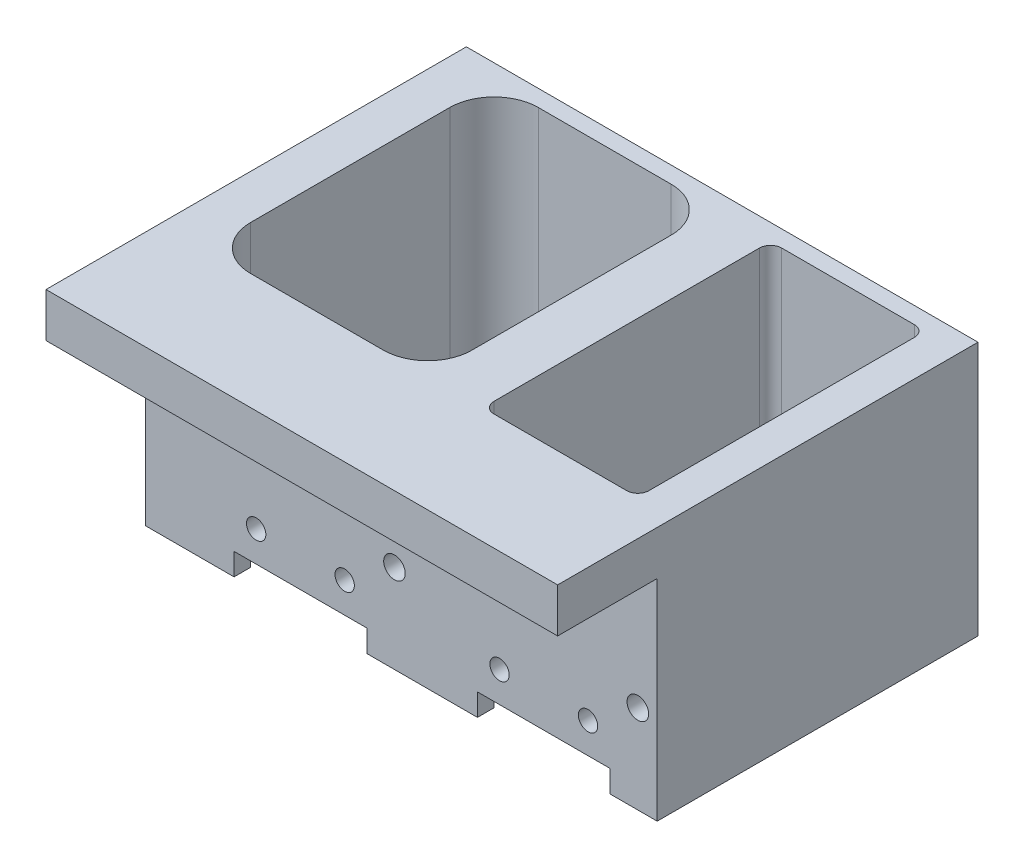
SolidWorks part; units mm, degrees
ref_plane "Front Plane" through (0, 0, 0) normal (0, 0, 1) x (1, 0, 0)
ref_plane "Top Plane" through (0, 0, 0) normal (0, 1, 0) x (1, 0, 0)
ref_plane "Right Plane" through (0, 0, 0) normal (1, 0, 0) x (0, 0, -1)
sketch "Sketch1" plane through (0, 0, 0) normal (0, 1, 0) x (1, 0, 0)
  line L1 (202.5, -147.5) -> (-202.5, -147.5)
  line L2 (202.5, -147.5) -> (202.5, 147.5)
  line L3 (202.5, 147.5) -> (-202.5, 147.5)
  line L4 (-202.5, -147.5) -> (-202.5, 147.5)
  line L5 (202.5, -147.5) -> (-202.5, 147.5) construction
  line L6 (202.5, 147.5) -> (-202.5, -147.5) construction
  point P0 (0, 0)
  dimension "D1" = 405
  dimension "D2" = 295
extrude "Boss-Extrude1" add sketch "Sketch1" along normal blind 53
sketch "Sketch3" plane through (0, 0, 0) normal (0, -1, 0) x (-1, 0, 0)
  line L23 (184.5, -129.5) -> (184.5, 129.5)
  line L24 (184.5, 129.5) -> (-184.5, 129.5)
  line L25 (-184.5, 129.5) -> (-184.5, -129.5)
  line L26 (-184.5, -129.5) -> (184.5, -129.5)
  line L27 (184.5, -129.5) -> (184.5, 129.5)
  line L28 (184.5, 129.5) -> (-184.5, 129.5)
  line L29 (-184.5, 129.5) -> (-184.5, -129.5)
  line L30 (-184.5, -129.5) -> (184.5, -129.5)
  dimension "D1" = 18
extrude "Cut-Extrude2" cut sketch "Sketch3" against normal blind 45 flip side to cut
sketch "Sketch2" plane through (0, 53, 0) normal (0, 1, 0) x (1, 0, 0)
  line L1 (-173.5, -126.5) -> (-105.5, -126.5)
  line L2 (-181.5, -118.5) -> (-181.5, -49.5)
  line L3 (-173.5, -41.5) -> (-105.5, -41.5)
  line L4 (-97.5, -118.5) -> (-97.5, -49.5)
  line L5 (-173.5, -31.5) -> (-105.5, -31.5)
  line L6 (-181.5, -23.5) -> (-181.5, 40.5)
  line L7 (-173.5, 48.5) -> (-105.5, 48.5)
  line L8 (-181.5, 126.5) -> (-181.5, -126.5)
  line L9 (-181.5, -126.5) -> (181.5, -126.5)
  line L10 (181.5, -126.5) -> (181.5, 126.5)
  line L11 (181.5, 126.5) -> (-181.5, 126.5)
  line L12 (-181.5, 126.5) -> (-181.5, -126.5) construction
  line L13 (-181.5, -126.5) -> (181.5, -126.5) construction
  line L14 (181.5, -126.5) -> (181.5, 126.5) construction
  line L15 (181.5, 126.5) -> (-181.5, 126.5) construction
  line L16 (-97.5, -23.5) -> (-97.5, 40.5)
  line L17 (-173.5, 126.5) -> (-105.5, 126.5)
  line L18 (-181.5, 118.5) -> (-181.5, 66.5)
  line L19 (-173.5, 58.5) -> (-105.5, 58.5)
  line L20 (-97.5, 118.5) -> (-97.5, 66.5)
  line L21 (173.5, -126.5) -> (115.5, -126.5)
  line L22 (181.5, -118.5) -> (181.5, 7.5)
  line L23 (173.5, 15.5) -> (115.5, 15.5)
  line L24 (107.5, -118.5) -> (107.5, 7.5)
  line L25 (173.5, 126.5) -> (107.5, 126.5)
  line L26 (181.5, 118.5) -> (181.5, 33.5)
  line L27 (173.5, 25.5) -> (107.5, 25.5)
  line L28 (99.5, 118.5) -> (99.5, 33.5)
  line L29 (81.5, 126.5) -> (20.5, 126.5)
  line L30 (89.5, 118.5) -> (89.5, -7.5)
  line L31 (81.5, -15.5) -> (20.5, -15.5)
  line L32 (12.5, 118.5) -> (12.5, -7.5)
  line L33 (-9.5, 126.5) -> (-31.5, 126.5)
  line L34 (-1.5, 118.5) -> (-1.5, 11.5)
  line L35 (-9.5, 3.5) -> (-31.5, 3.5)
  line L36 (-39.5, 118.5) -> (-39.5, 11.5)
  line L37 (-57.5, 126.5) -> (-79.5, 126.5)
  line L38 (-49.5, 118.5) -> (-49.5, 11.5)
  line L39 (-57.5, 3.5) -> (-79.5, 3.5)
  line L40 (-87.5, 118.5) -> (-87.5, 11.5)
  line L41 (-79.5, -15.5) -> (-55.5, -15.5)
  line L42 (-81.5, -17.5) -> (-81.5, -65.5)
  line L43 (-79.5, -67.5) -> (-55.5, -67.5)
  line L44 (-53.5, -17.5) -> (-53.5, -65.5)
  line L45 (-73.5, -126.5) -> (-49.5, -126.5)
  line L46 (-81.5, -118.5) -> (-81.5, -82.5)
  line L47 (-73.5, -74.5) -> (-49.5, -74.5)
  line L48 (-41.5, -118.5) -> (-41.5, -82.5)
  line L49 (-35.5, -15.5) -> (-11.5, -15.5)
  line L50 (-43.5, -23.5) -> (-43.5, -59.5)
  line L51 (-35.5, -67.5) -> (-11.5, -67.5)
  line L52 (-3.5, -23.5) -> (-3.5, -59.5)
  line L53 (-29.5, -74.5) -> (-5.5, -74.5)
  line L54 (-31.5, -76.5) -> (-31.5, -124.5)
  line L55 (-29.5, -126.5) -> (-5.5, -126.5)
  line L56 (-3.5, -76.5) -> (-3.5, -124.5)
  line L57 (89.5, -126.5) -> (19.5, -126.5)
  line L58 (97.5, -118.5) -> (97.5, -33.5)
  line L59 (89.5, -25.5) -> (19.5, -25.5)
  line L60 (11.5, -118.5) -> (11.5, -33.5)
  arc A0 (-79.5, 126.5) -> (-87.5, 118.5) centre (-79.5, 118.5) ccw
  arc A1 (-79.5, 3.5) -> (-87.5, 11.5) centre (-79.5, 11.5) cw
  arc A2 (-49.5, 11.5) -> (-57.5, 3.5) centre (-57.5, 11.5) cw
  arc A3 (-57.5, 126.5) -> (-49.5, 118.5) centre (-57.5, 118.5) cw
  arc A4 (-31.5, 126.5) -> (-39.5, 118.5) centre (-31.5, 118.5) ccw
  arc A5 (-31.5, 3.5) -> (-39.5, 11.5) centre (-31.5, 11.5) cw
  arc A6 (-1.5, 11.5) -> (-9.5, 3.5) centre (-9.5, 11.5) cw
  arc A7 (-9.5, 126.5) -> (-1.5, 118.5) centre (-9.5, 118.5) cw
  arc A8 (20.5, 126.5) -> (12.5, 118.5) centre (20.5, 118.5) ccw
  arc A9 (20.5, -15.5) -> (12.5, -7.5) centre (20.5, -7.5) cw
  arc A10 (89.5, -7.5) -> (81.5, -15.5) centre (81.5, -7.5) cw
  arc A11 (81.5, 126.5) -> (89.5, 118.5) centre (81.5, 118.5) cw
  arc A12 (107.5, 126.5) -> (99.5, 118.5) centre (107.5, 118.5) ccw
  arc A13 (173.5, 126.5) -> (181.5, 118.5) centre (173.5, 118.5) cw
  arc A14 (181.5, 33.5) -> (173.5, 25.5) centre (173.5, 33.5) cw
  arc A15 (107.5, 25.5) -> (99.5, 33.5) centre (107.5, 33.5) cw
  arc A16 (115.5, 15.5) -> (107.5, 7.5) centre (115.5, 7.5) ccw
  arc A17 (181.5, 7.5) -> (173.5, 15.5) centre (173.5, 7.5) ccw
  arc A18 (173.5, -126.5) -> (181.5, -118.5) centre (173.5, -118.5) ccw
  arc A19 (115.5, -126.5) -> (107.5, -118.5) centre (115.5, -118.5) cw
  arc A20 (89.5, -126.5) -> (97.5, -118.5) centre (89.5, -118.5) ccw
  arc A21 (97.5, -33.5) -> (89.5, -25.5) centre (89.5, -33.5) ccw
  arc A22 (19.5, -25.5) -> (11.5, -33.5) centre (19.5, -33.5) ccw
  arc A23 (19.5, -126.5) -> (11.5, -118.5) centre (19.5, -118.5) cw
  arc A28 (-43.5, -59.5) -> (-35.5, -67.5) centre (-35.5, -59.5) ccw
  arc A29 (-11.5, -67.5) -> (-3.5, -59.5) centre (-11.5, -59.5) ccw
  arc A30 (-11.5, -15.5) -> (-3.5, -23.5) centre (-11.5, -23.5) cw
  arc A31 (-35.5, -15.5) -> (-43.5, -23.5) centre (-35.5, -23.5) ccw
  arc A36 (-49.5, -74.5) -> (-41.5, -82.5) centre (-49.5, -82.5) cw
  arc A37 (-49.5, -126.5) -> (-41.5, -118.5) centre (-49.5, -118.5) ccw
  arc A38 (-73.5, -126.5) -> (-81.5, -118.5) centre (-73.5, -118.5) cw
  arc A39 (-81.5, -82.5) -> (-73.5, -74.5) centre (-73.5, -82.5) cw
  arc A40 (-105.5, -41.5) -> (-97.5, -49.5) centre (-105.5, -49.5) cw
  arc A41 (-105.5, -126.5) -> (-97.5, -118.5) centre (-105.5, -118.5) ccw
  arc A42 (-173.5, -126.5) -> (-181.5, -118.5) centre (-173.5, -118.5) cw
  arc A43 (-181.5, -49.5) -> (-173.5, -41.5) centre (-173.5, -49.5) cw
  arc A44 (-105.5, 48.5) -> (-97.5, 40.5) centre (-105.5, 40.5) cw
  arc A45 (-105.5, -31.5) -> (-97.5, -23.5) centre (-105.5, -23.5) ccw
  arc A46 (-173.5, -31.5) -> (-181.5, -23.5) centre (-173.5, -23.5) cw
  arc A47 (-181.5, 40.5) -> (-173.5, 48.5) centre (-173.5, 40.5) cw
  arc A48 (-105.5, 126.5) -> (-97.5, 118.5) centre (-105.5, 118.5) cw
  arc A49 (-105.5, 58.5) -> (-97.5, 66.5) centre (-105.5, 66.5) ccw
  arc A50 (-181.5, 66.5) -> (-173.5, 58.5) centre (-173.5, 66.5) ccw
  arc A51 (-173.5, 126.5) -> (-181.5, 118.5) centre (-173.5, 118.5) ccw
  arc A52 (-81.5, -17.5) -> (-79.5, -15.5) centre (-79.5, -17.5) cw
  arc A53 (-79.5, -67.5) -> (-81.5, -65.5) centre (-79.5, -65.5) cw
  arc A54 (-53.5, -65.5) -> (-55.5, -67.5) centre (-55.5, -65.5) cw
  arc A55 (-55.5, -15.5) -> (-53.5, -17.5) centre (-55.5, -17.5) cw
  arc A56 (-3.5, -76.5) -> (-5.5, -74.5) centre (-5.5, -76.5) ccw
  arc A57 (-5.5, -126.5) -> (-3.5, -124.5) centre (-5.5, -124.5) ccw
  arc A58 (-31.5, -124.5) -> (-29.5, -126.5) centre (-29.5, -124.5) ccw
  arc A59 (-31.5, -76.5) -> (-29.5, -74.5) centre (-29.5, -76.5) cw
  point P54 (-87.5, 126.5)
  point P57 (-87.5, 3.5)
  point P62 (-49.5, 126.5)
  point P65 (-39.5, 126.5)
  point P72 (-1.5, 126.5)
  point P75 (12.5, 126.5)
  point P82 (89.5, 126.5)
  point P85 (99.5, 126.5)
  point P91 (181.5, 25.5)
  point P103 (107.5, -126.5)
  point P106 (97.5, -126.5)
  point P109 (97.5, -25.5)
  point P114 (11.5, -126.5)
  point P119 (-3.5, -126.5)
  point P122 (-31.5, -126.5)
  point P127 (-43.5, -67.5)
  point P130 (-3.5, -67.5)
  point P139 (-81.5, -15.5)
  point P142 (-81.5, -67.5)
  point P149 (-41.5, -126.5)
  point P152 (-81.5, -126.5)
  point P155 (-81.5, -74.5)
  point P171 (-181.5, -31.5)
  point P174 (-181.5, 48.5)
  point P177 (-97.5, 126.5)
  point P182 (-181.5, 58.5)
  point P188 (-81.5, -15.5)
  point P191 (-81.5, -67.5)
  point P200 (-3.5, -126.5)
  point P203 (-31.5, -126.5)
  dimension "D31" = 8
  dimension "D32" = 8
  dimension "D33" = 8
  dimension "D34" = 2
  dimension "D35" = 2
  dimension "D2" = 74
  dimension "D3" = 82
  dimension "D4" = 101
  dimension "D5" = 10
  dimension "D6" = 86
  dimension "D7" = 10
  dimension "D8" = 15
  dimension "D9" = 28
  dimension "D10" = 40
  dimension "D11" = 52
  dimension "D12" = 52
  dimension "D13" = 77
  dimension "D14" = 38
  dimension "D15" = 38
  dimension "D16" = 84
  dimension "D17" = 68
  dimension "D18" = 80
  dimension "D19" = 10
  dimension "D20" = 10
  dimension "D21" = 7
  dimension "D22" = 10
  dimension "D23" = 101
  dimension "D24" = 10
  dimension "D25" = 10
  dimension "D26" = 123
  dimension "D27" = 10
  dimension "D28" = 10
  dimension "D29" = 40
  dimension "D30" = 10
  dimension "D1" = 21
extrude "Mini bin cuts" cut sketch "Sketch2" against normal blind 46
fillet "Fillet1" radius 8 4 edges at (-184.5, 22.5, -129.5) (184.5, 22.5, -129.5) (184.5, 22.5, 129.5) (-184.5, 22.5, 129.5)
sketch "Sketch6" plane through (-184.5, 0, 0) normal (-1, 0, 0) x (0, 0, 1)
  line L0 (129.5, 45) -> (129.5, 0) construction
  line L1 (-129.5, 0) -> (129.5, 0)
  line L2 (-129.5, 0) -> (-129.5, 7)
  line L3 (-129.5, 7) -> (129.5, 7)
  line L4 (129.5, 0) -> (129.5, 7)
  dimension "D1" = 7
extrude "Cut-Extrude5" cut sketch "Sketch6" against normal through all
sketch "Sketch8" plane through (0, 0, 129.5) normal (0, 0, 1) x (1, 0, 0)
  line L0 (-176.5, 16.5) -> (176.5, 16.5) construction
  line L1 (-176.5, 45) -> (-176.5, 7) construction
  line L2 (176.5, 7) -> (176.5, 45) construction
  line L3 (173.5, 53) -> (115.5, 53) construction
  line L4 (89.5, 53) -> (19.5, 53) construction
  line L5 (-61.5, 45) -> (-61.5, 7) construction
  line L6 (176.5, 45) -> (-176.5, 45) construction
  line L7 (176.5, 7) -> (-176.5, 7) construction
  line L8 (-17.5, 45) -> (-17.5, 7) construction
  line L9 (-29.5, 53) -> (-5.5, 53) construction
  line L10 (-73.5, 53) -> (-49.5, 53) construction
  line L11 (144.5, 45) -> (144.5, 7) construction
  line L12 (54.5, 45) -> (54.5, 7) construction
  circle A0 centre (-69.5, 16.5) radius 1.75
  circle A1 centre (-25.5, 16.5) radius 1.75
  circle A2 centre (46.5, 16.5) radius 1.75
  circle A3 centre (136.5, 16.5) radius 1.75
  circle A4 centre (152.5, 16.5) radius 1.75
  circle A5 centre (62.5, 16.5) radius 1.75
  circle A6 centre (-9.5, 16.5) radius 1.75
  circle A7 centre (-53.5, 16.5) radius 1.75
  circle A8 centre (-44.5, 23) radius 1.95
  circle A9 centre (-0.5, 23) radius 1.95
  circle A10 centre (71.5, 23) radius 1.95
  circle A11 centre (161.5, 23) radius 1.95
  point P45 (144.5, 53)
  point P49 (54.5, 53)
  point P53 (-17.5, 53)
  point P57 (-61.5, 53)
  dimension "D5" = 3.5
  dimension "D6" = 3.5
  dimension "D7" = 3.5
  dimension "D8" = 3.5
  dimension "D14" = 3.9
  dimension "D16" = 6.5
  dimension "D17" = 17
  dimension "D19" = 17
  dimension "D3" = 9.5
  dimension "D9" = 8
  dimension "D10" = 8
  dimension "D11" = 8
  dimension "D12" = 8
  dimension "D15" = 17
  dimension "D21" = 17
extrude "Holes Lids 8,9,12,13" cut sketch "Sketch8" against normal up to surface (3 mm away) up to face at (54.5, 30, 126.5)
sketch "Sketch9" plane through (0, 0, 147.5) normal (0, 0, 1) x (1, 0, 0)
  line L0 (176.5, 7) -> (-176.5, 7) construction
  line L1 (-202.5, 53) -> (-89.5, 53)
  line L2 (-202.5, 53) -> (-202.5, 7)
  line L3 (-202.5, 7) -> (-89.5, 7)
  line L4 (-89.5, 53) -> (-89.5, 7)
  line L5 (202.5, 53) -> (3, 53)
  line L6 (202.5, 53) -> (202.5, 7)
  line L7 (202.5, 7) -> (3, 7)
  line L8 (3, 53) -> (3, 7)
  line L9 (-202.5, 53) -> (202.5, 53) construction
  line L10 (-73.5, 53) -> (-49.5, 53) construction
  point P15 (0, 53)
  point P16 (0, 0)
  point P17 (-92.1864, 12.7604)
  point P20 (-61.5, 53)
  dimension "D1" = 3
  dimension "D2" = 28
extrude "Cut-Extrude6" cut sketch "Sketch9" against normal through all
sketch "Sketch10" plane through (3, 0, 0) normal (1, 0, 0) x (0, 0, -1)
  line L0 (129.5, 7) -> (-129.5, 7) construction
  line L1 (147.5, 53) -> (-71.5, 53)
  line L2 (147.5, 53) -> (147.5, 7)
  line L3 (147.5, 7) -> (-71.5, 7)
  line L4 (-71.5, 53) -> (-71.5, 7)
  line L5 (-124.5, 7) -> (-76.5, 7) construction
  point P9 (-100.5, 7)
  dimension "D1" = 29
extrude "Cut-Extrude7" cut sketch "Sketch10" against normal through all
sketch "Sketch11" plane through (0, 0, 129.5) normal (0, 0, 1) x (1, 0, 0)
  line L0 (3, 7) -> (-89.5, 7) construction
  line L1 (-73.5, 7) -> (-49.5, 7)
  line L2 (-73.5, 7) -> (-73.5, 11)
  line L3 (-73.5, 11) -> (-49.5, 11)
  line L4 (-49.5, 7) -> (-49.5, 11)
  line L6 (-29.5, 7) -> (-5.5, 7)
  line L7 (-29.5, 7) -> (-29.5, 11)
  line L8 (-29.5, 11) -> (-5.5, 11)
  line L9 (-5.5, 7) -> (-5.5, 11)
  circle A0 centre (-69.5, 16.5) radius 1.75 construction
  circle A1 centre (-53.5, 16.5) radius 1.75 construction
  circle A3 centre (-25.5, 16.5) radius 1.75 construction
  circle A4 centre (-9.5, 16.5) radius 1.75 construction
  dimension "D2" = 4
  dimension "D4" = 4
  dimension "D1" = 4
  dimension "D3" = 4
  dimension "D5" = 4
extrude "Cut-Extrude8" cut sketch "Sketch11" against normal up to surface (3 mm away) up to face at (-67.75, 16.5, 126.5)
